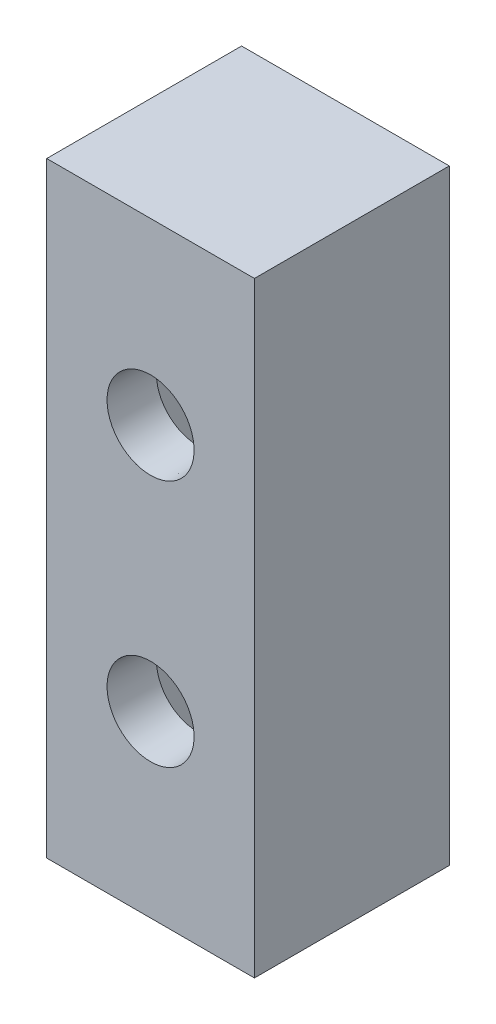
SolidWorks part; units mm, degrees
material "PET"
ref_plane "Front Plane" through (0, 0, 0) normal (0, 0, 1) x (1, 0, 0)
ref_plane "Top Plane" through (0, 0, 0) normal (0, 1, 0) x (1, 0, 0)
ref_plane "Right Plane" through (0, 0, 0) normal (1, 0, 0) x (0, 0, -1)
sketch "Sketch1" plane through (0, 0, 0) normal (0, 0, 1) x (1, 0, 0)
  line L4 (64.275, -16) -> (64.275, 16)
  line L5 (64.275, 16) -> (54.75, 16)
  line L6 (54.75, 16) -> (54.75, -16)
  line L7 (54.75, -16) -> (64.275, -16)
  line L8 (64.275, -16) -> (64.275, 16)
  line L9 (64.275, 16) -> (54.75, 16)
  line L10 (54.75, 16) -> (54.75, -16)
  line L11 (54.75, -16) -> (64.275, -16)
  circle A0 centre (59.5125, -7) radius 3.1 construction
  circle A1 centre (59.5125, 7) radius 3.1 construction
  circle A2 centre (59.5125, -7) radius 3.1 construction
  circle A3 centre (59.5125, 7) radius 3.1 construction
  dimension "D1" = 0
extrude "Boss-Extrude1" add sketch "Sketch1" along normal blind 3
sketch "Sketch2" plane through (0, 0, 3) normal (0, 0, 1) x (1, 0, 0)
  line L0 (53.65, 17.1) -> (53.65, -17.1)
  line L1 (53.65, -17.1) -> (65.375, -17.1)
  line L2 (65.375, -17.1) -> (65.375, 17.1)
  line L3 (65.375, 17.1) -> (53.65, 17.1)
  line L4 (54.75, -16) -> (64.275, -16)
  line L5 (64.275, -16) -> (64.275, 16)
  line L6 (64.275, 16) -> (54.75, 16)
  line L7 (54.75, 16) -> (54.75, -16)
  line L8 (54.75, -16) -> (64.275, -16)
  line L9 (64.275, -16) -> (64.275, 16)
  line L10 (64.275, 16) -> (54.75, 16)
  line L11 (54.75, 16) -> (54.75, -16)
  dimension "D1" = 0
  dimension "D2" = 1.1
extrude "Boss-Extrude2" add sketch "Sketch2" against normal offset from surface (11 mm away) 8 up to face at (59.5125, 0, 0) offset beyond the face yes
sketch "Sketch3" plane through (0, 0, 0) normal (0, 0, -1) x (-1, 0, 0)
  circle A0 centre (-59.5125, 7) radius 2.3
  circle A1 centre (-59.5125, -7) radius 2.3
  dimension "D1" = 4.6
extrude "Cut-Extrude1" cut sketch "Sketch3" against normal through all draft 3 draft outward yes
other "Move Face1" face at (59.5125, -16, -4) face at (54.75, 0, -4) face at (64.275, 0, -4) face at (59.5125, 16, -4) face at (57.2125, 7, 0) parameters "D1"=0.35
